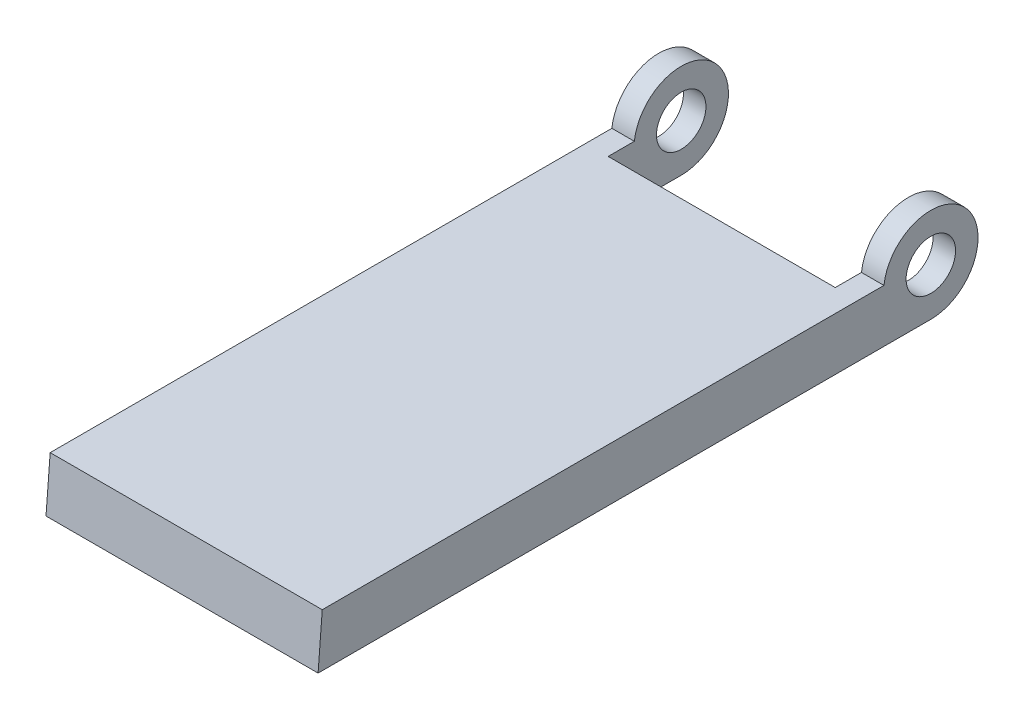
SolidWorks part; units mm, degrees
ref_plane "前视基准面" through (0, 0, 0) normal (0, 0, 1) x (1, 0, 0)
ref_plane "上视基准面" through (0, 0, 0) normal (0, 1, 0) x (1, 0, 0)
ref_plane "右视基准面" through (0, 0, 0) normal (1, 0, 0) x (0, 0, -1)
other "Configuration Table"
sketch "草图1" plane through (0, 0, 0) normal (0, 1, 0) x (1, 0, 0)
  line L1 (0, 0) -> (20.2, 0)
  line L2 (0, 0) -> (0, -30)
  line L3 (0, -30) -> (20.2, -30)
  line L4 (20.2, 0) -> (20.2, -30)
  dimension "D1" = 20.2
  dimension "D2" = 30
extrude "凸台-拉伸1" add sketch "草图1" along normal blind 2
sketch "草图2" plane through (0, 0, 0) normal (-1, 0, 0) x (0, 0, 1)
  line L0 (0, 2) -> (30, 2) construction
  line L1 (0, 2) -> (0, 0) construction
  circle A0 centre (-2.5, 1.5) radius 2.2
  circle A2 centre (-2.5, 1.5) radius 4.2
  dimension "D1" = 4.4
  dimension "D2" = 0.5
  dimension "D3" = 2.5
  dimension "D4" = 2
extrude "凸台-拉伸2" add sketch "草图2" along normal blind 2
ref_plane "基准面1" through (10.1, 0, 0) normal (1, 0, 0) x (0, 0, -1)
sketch "草图3" plane through (0, 0, 0) normal (-1, 0, 0) x (0, 0, 1)
  line L5 (1.423, 0) -> (30, 0)
  line L6 (30, 0) -> (30, 2)
  line L7 (30, 2) -> (1.6701, 2)
  line L9 (1.423, 0) -> (30, 0)
  line L10 (30, 0) -> (30, 2)
  line L11 (30, 2) -> (1.6701, 2)
  arc A1 (1.423, 0) -> (1.6701, 2) centre (-2.5, 1.5) ccw
  arc A2 (1.423, 0) -> (1.6701, 2) centre (-2.5, 1.5) ccw
  dimension "D1" = 0
extrude "凸台-拉伸3" add sketch "草图3" along normal up to surface (2 mm away) up to face at (-2, 1.5, 1.7)
mirror "镜向1" about plane through (10.1, 0, 0) normal (1, 0, 0) of "凸台-拉伸3", "凸台-拉伸2"
sketch "草图4" plane through (0, 2, 0) normal (0, 1, 0) x (1, 0, 0)
  line L0 (20.2, 6.7) -> (20.2, -1.6701) construction
  line L1 (0, 0) -> (20.2, 0)
  line L2 (0, 0) -> (0, -4)
  line L3 (0, -4) -> (20.2, -4)
  line L4 (20.2, 0) -> (20.2, -4)
  point P4 (20.2, 0)
  dimension "D1" = 4
extrude "切除-拉伸1" cut sketch "草图4" against normal up to next
sketch "草图5" plane through (-2, 0, 0) normal (-1, 0, 0) x (0, 0, 1)
  line L0 (-2.5, 1.5) -> (-5.3682, 2.3794) construction
  line L1 (-5.3682, 2.3794) -> (-0.0916, 19.5887) construction
  line L2 (1.6701, 2) -> (57.2725, 2) construction
  line L3 (-0.0916, 19.5887) -> (57.2725, 2) construction
  dimension "D1" = 3
  dimension "D2" = 18
  dimension "D3" = 60
sketch "草图7" plane through (-2, 0, 0) normal (-1, 0, 0) x (0, 0, 1)
  line L0 (30, 0) -> (56.6593, 0)
  line L1 (56.6593, 0) -> (57.2725, 2)
  line L2 (1.6701, 2) -> (57.2725, 2) construction
  line L3 (57.2725, 2) -> (30, 2)
  line L4 (30, 2) -> (30, 0)
  line L5 (-0.0916, 19.5887) -> (57.2725, 2) construction
  point P13 (57.2725, 2)
extrude "凸台-拉伸4" add sketch "草图7" against normal up to surface (24.2 mm away) up to face at (22.2, 1.5, -0.3)
sketch "草图8" plane through (20.2, 0, 0) normal (-1, 0, 0) x (0, 0, 1)
  line L0 (4, 2) -> (3.3868, 0)
  line L1 (1.423, 0) -> (4, 0) construction
  line L2 (3.3868, 0) -> (4, 0)
  line L3 (4, 0) -> (4, 2)
  line L4 (-5.3682, 2.3794) -> (-0.0916, 19.5887) construction
extrude "凸台-拉伸5" add sketch "草图8" along normal up to surface (20.2 mm away) up to face at (0, 1.2538, 0.7196)
sketch "草图10" plane through (-2, 0, 0) normal (-1, 0, 0) x (0, 0, 1)
  line L0 (56.6593, 0) -> (55.8314, -2.7)
  line L1 (55.8314, -2.7) -> (-2.5, -2.7)
  line L2 (1.423, 0) -> (56.6593, 0)
  line L3 (56.6593, 0) -> (57.2725, 2) construction
  arc A0 (1.6701, 2) -> (1.423, 0) centre (-2.5, 1.5) ccw construction
  arc A1 (-2.5, -2.7) -> (1.423, 0) centre (-2.5, 1.5) ccw
  point P7 (-1.4764, -2.5734)
extrude "凸台-拉伸6" add sketch "草图10" against normal up to surface (24.2 mm away) up to face at (22.2, 1.5, -0.3)
sketch "草图11" plane through (20.2, 0, 0) normal (-1, 0, 0) x (0, 0, 1)
  line L0 (3.3868, 0) -> (2.5589, -2.7)
  line L1 (2.5589, -2.7) -> (-2.5, -2.7)
  line L2 (-2.5, -2.7) -> (1.423, 0)
  line L3 (1.423, 0) -> (3.3868, 0)
  line L4 (4, 2) -> (3.3868, 0) construction
extrude "切除-拉伸2" cut sketch "草图11" along normal up to surface (20.2 mm away) up to face at (0, 1.5, -0.3)
sketch "草图12" plane through (0, -15.8797, 51.7903) normal (0, -0.2931, 0.9561) x (1, 0, 0)
  line L0 (10.1, 18.7012) -> (10.1, 38.7012) construction
  line L1 (22.2, 18.7012) -> (-2, 18.7012) construction
  line L2 (10.1, -55) -> (10.1, 55) construction
  line L3 (10.1, 38.7012) -> (-9.9, 38.7012) construction
  line L4 (-9.9, 38.7012) -> (-9.9, -1.2988) construction
  line L5 (-9.9, -1.2988) -> (30.1, -1.2988) construction
  line L6 (30.1, -1.2988) -> (30.1, 38.7012) construction
  line L7 (30.1, 38.7012) -> (10.1, 38.7012) construction
  dimension "D1" = 20
  dimension "D2" = 20
  dimension "D3" = 20
  dimension "D4" = 40
sketch "草图14" plane through (-2, 0, 0) normal (-1, 0, 0) x (0, 0, 1)
  line L3 (-2.5, 1.5) -> (-5.4907, 1.2638) construction
  line L4 (-5.4907, 1.2638) -> (-6.9078, 19.2079) construction
  line L5 (-6.9078, 19.2079) -> (52.9059, 23.9317) construction
  line L6 (-2.5, 1.5) -> (-5.3682, 2.3794) construction
  line L7 (-5.3682, 2.3794) -> (-0.0916, 19.5887) construction
  line L8 (-0.0916, 19.5887) -> (57.2725, 2) construction
  line L9 (1.6701, 2) -> (57.2725, 2) construction
  line L10 (52.9059, 23.9317) -> (54.638, 2) construction
  point P11 (47.802, 30.5604)
  point P12 (54.638, 2)
  dimension "D1" = 22
sketch "草图15" plane through (-2, 0, 0) normal (-1, 0, 0) x (0, 0, 1)
  line L0 (51.6286, 2) -> (51.9998, -2.7)
  line L1 (1.6701, 2) -> (57.2725, 2) construction
  line L2 (-2.5, -2.7) -> (55.8314, -2.7) construction
  line L3 (51.9998, -2.7) -> (55.8314, -2.7)
  line L4 (55.8314, -2.7) -> (57.2725, 2)
  line L5 (51.4096, -17.1214) -> (63.1354, 21.1214) construction
  line L6 (57.2725, 2) -> (51.6286, 2)
  line L7 (52.9059, 23.9317) -> (54.638, 2) construction
  dimension "D1" = 3
extrude "切除-拉伸3" cut sketch "草图15" against normal up to next
